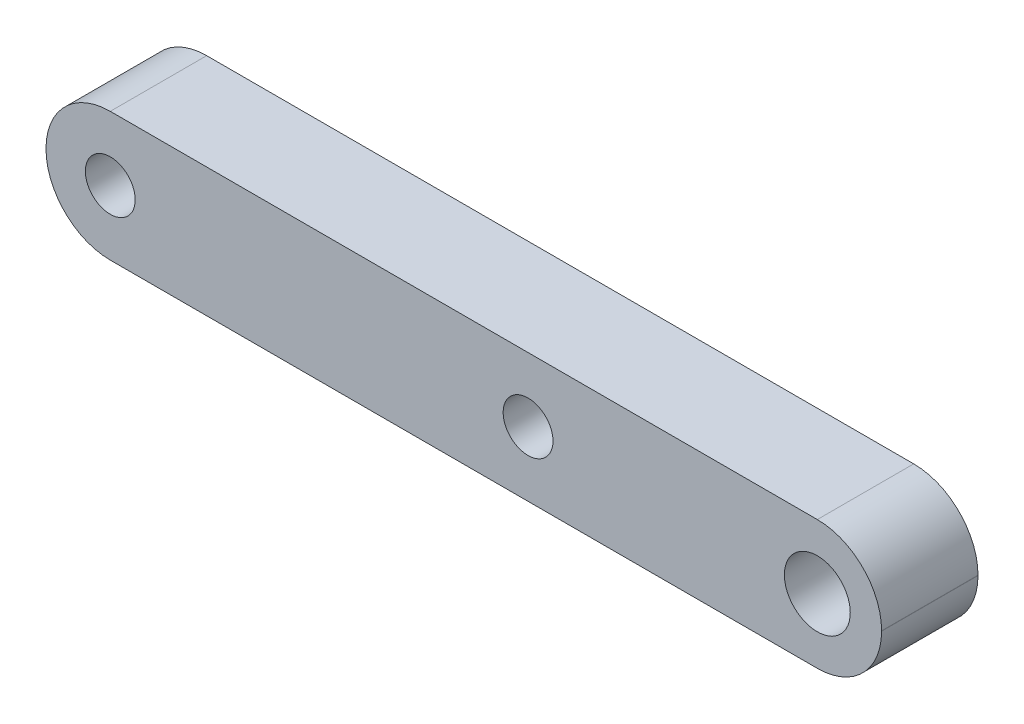
SolidWorks part; units mm, degrees
ref_plane "Płaszczyzna przednia" through (0, 0, 0) normal (0, 0, 1) x (1, 0, 0)
ref_plane "Płaszczyzna górna" through (0, 0, 0) normal (0, 1, 0) x (1, 0, 0)
ref_plane "Płaszczyzna prawa" through (0, 0, 0) normal (1, 0, 0) x (0, 0, -1)
sketch "Szkic1" plane through (0, 0, 0) normal (0, 0, 1) x (1, 0, 0)
  line L0 (148.39, 90.2043) -> (148.39, 90.1843)
  line L1 (152.39, 94.2043) -> (196.39, 94.2043)
  line L2 (152.39, 86.1843) -> (196.39, 86.1843)
  line L3 (200.39, 90.2043) -> (200.39, 90.1843)
  arc A0 (196.39, 86.1843) -> (200.39, 90.1843) centre (196.39, 90.1843) ccw
  arc A1 (196.39, 94.2043) -> (200.39, 90.2043) centre (196.39, 90.2043) cw
  arc A2 (148.39, 90.1843) -> (152.39, 86.1843) centre (152.39, 90.1843) ccw
  arc A3 (152.39, 94.2043) -> (148.39, 90.2043) centre (152.39, 90.2043) ccw
  dimension "D2" = 4
  dimension "D1" = 52
extrude "Dodanie-wyciągnięcie1" add sketch "Szkic1" along normal blind 6
sketch "Szkic2" plane through (0, 0, 6) normal (0, 0, 1) x (1, 0, 0)
  circle A3 centre (196.39, 90.2043) radius 2.05 construction
  circle A4 centre (178.39, 90.2043) radius 1.55 construction
  circle A5 centre (152.39, 90.2043) radius 1.55 construction
  circle A6 centre (196.39, 90.2043) radius 2.05
  circle A7 centre (178.39, 90.2043) radius 1.55
  circle A8 centre (152.39, 90.2043) radius 1.55
extrude "Wytnij-wyciągnięcie1" cut sketch "Szkic2" against normal blind 6
